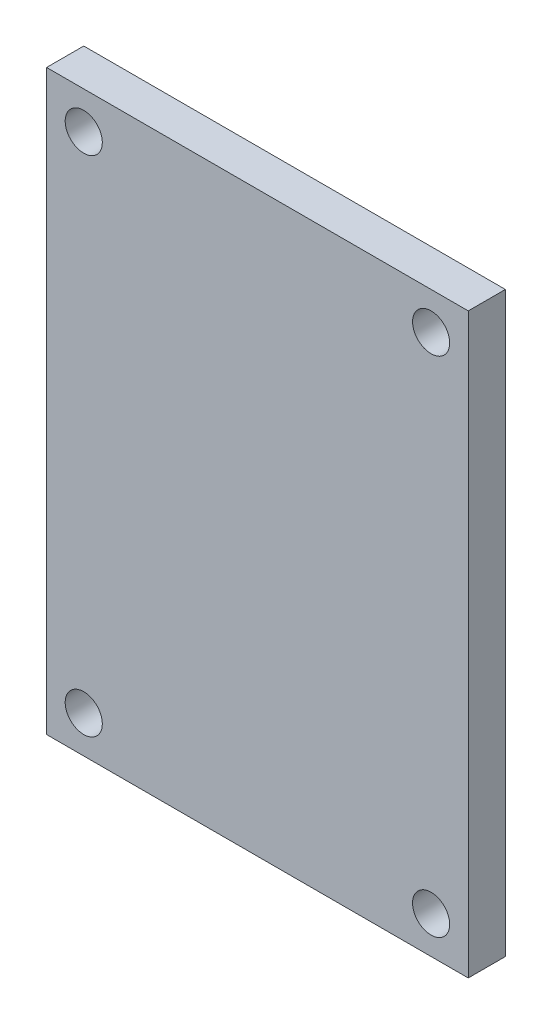
SolidWorks part; units mm, degrees
material "Acrylic (Medium-high impact)"
ref_plane "Front Plane" through (0, 0, 0) normal (0, 0, 1) x (1, 0, 0)
ref_plane "Top Plane" through (0, 0, 0) normal (0, 1, 0) x (1, 0, 0)
ref_plane "Right Plane" through (0, 0, 0) normal (1, 0, 0) x (0, 0, -1)
sketch "Sketch1" plane through (0, 0, 0) normal (0, 0, 1) x (1, 0, 0)
  line L1 (-17.03, -23.335) -> (17.03, -23.335)
  line L2 (-17.03, -23.335) -> (-17.03, 23.335)
  line L3 (-17.03, 23.335) -> (17.03, 23.335)
  line L4 (17.03, -23.335) -> (17.03, 23.335)
  line L5 (-17.03, -23.335) -> (17.03, 23.335) construction
  line L6 (-17.03, 23.335) -> (17.03, -23.335) construction
  point P0 (0, 0)
  dimension "D1" = 46.67
  dimension "D2" = 34.06
extrude "Boss-Extrude1" add sketch "Sketch1" along normal blind 3
sketch "Sketch2" plane through (0, 0, 3) normal (0, 0, 1) x (1, 0, 0)
  line L0 (17.03, -23.335) -> (17.03, 23.335) construction
  line L1 (-14.03, -20.335) -> (14.03, -20.335) construction
  line L2 (-14.03, -20.335) -> (-14.03, 20.335) construction
  line L3 (-14.03, 20.335) -> (14.03, 20.335) construction
  line L4 (14.03, -20.335) -> (14.03, 20.335) construction
  line L5 (-14.03, -20.335) -> (14.03, 20.335) construction
  line L6 (-14.03, 20.335) -> (14.03, -20.335) construction
  line L7 (17.03, 23.335) -> (-17.03, 23.335) construction
  circle A0 centre (-14.03, 20.335) radius 1.5
  circle A1 centre (14.03, 20.335) radius 1.5
  circle A2 centre (14.03, -20.335) radius 1.5
  circle A3 centre (-14.03, -20.335) radius 1.5
  point P0 (0, 0)
  dimension "D3" = 3
  dimension "D1" = 3
  dimension "D2" = 3
extrude "Cut-Extrude1" cut sketch "Sketch2" against normal through all
